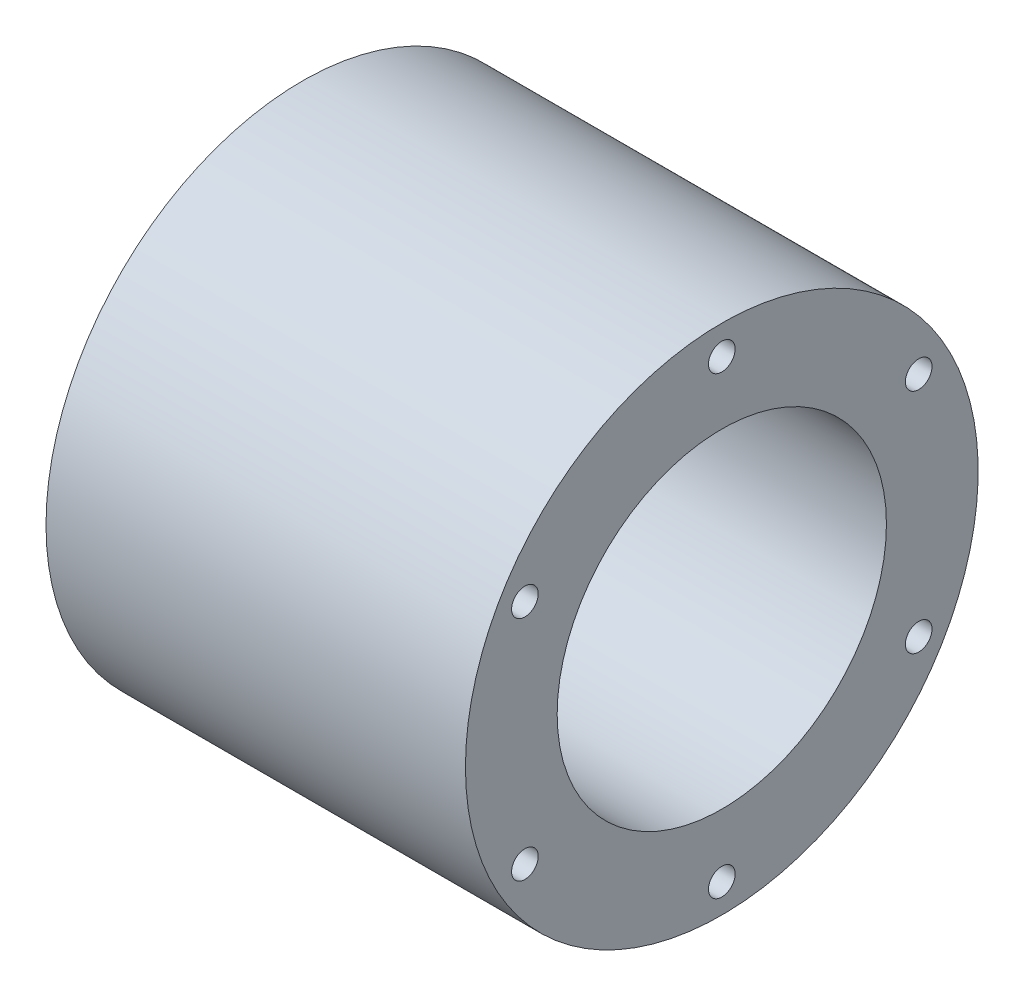
SolidWorks part; units mm, degrees
material "6063-T5"
ref_plane "Front" through (0, 0, 0) normal (0, 0, 1) x (1, 0, 0)
ref_plane "Top" through (0, 0, 0) normal (0, 1, 0) x (1, 0, 0)
ref_plane "Right" through (0, 0, 0) normal (1, 0, 0) x (0, 0, -1)
sketch "Croquis1" plane through (0, 0, 0) normal (1, 0, 0) x (0, 0, -1)
  circle A0 centre (0, 0) radius 21
  circle A1 centre (0, 0) radius 32.7
  dimension "D1" = 42
  dimension "D2" = 65.4
extrude "Saliente-Extruir1" add sketch "Croquis1" along normal mid plane 48.5
sketch "Croquis3" plane through (-24.25, 0, 0) normal (-1, 0, 0) x (0, 0, 1)
  line L6 (-18, -21) -> (18, -21)
  line L15 (-21, -18) -> (-21, 18)
  line L16 (-18, 21) -> (18, 21)
  line L17 (21, -18) -> (21, 18)
  line L18 (-21, -21) -> (21, 21) construction
  line L19 (-21, 21) -> (21, -21) construction
  circle A0 centre (0, 0) radius 32.7 construction
  circle A1 centre (0, 0) radius 32.7
  arc A2 (-18, -21) -> (-21, -18) centre (-18, -18) cw
  arc A3 (18, -21) -> (21, -18) centre (18, -18) ccw
  arc A4 (18, 21) -> (21, 18) centre (18, 18) cw
  arc A5 (-21, 18) -> (-18, 21) centre (-18, 18) cw
  dimension "D2" = 3
  dimension "D1" = 42
extrude "Saliente-Extruir3" add sketch "Croquis3" along normal blind 5
sketch "Croquis4" plane through (-24.25, 0, 0) normal (-1, 0, 0) x (0, 0, 1)
  line L1 (-15.5, -15.5) -> (15.5, -15.5) construction
  line L2 (-15.5, -15.5) -> (-15.5, 15.5) construction
  line L3 (-15.5, 15.5) -> (15.5, 15.5) construction
  line L4 (15.5, -15.5) -> (15.5, 15.5) construction
  line L5 (-15.5, -15.5) -> (15.5, 15.5) construction
  line L6 (-15.5, 15.5) -> (15.5, -15.5) construction
  circle A0 centre (15.5, 15.5) radius 3.5
  circle A1 centre (-15.5, 15.5) radius 3.5
  circle A2 centre (-15.5, -15.5) radius 3.5
  circle A3 centre (15.5, -15.5) radius 3.5
  point P0 (0, 0)
  dimension "D2" = 7
  dimension "D1" = 31
extrude "Cortar-Extruir1" cut sketch "Croquis4" against normal blind 6
hole_wizard "Taladro de margen para M31" positions "Croquis5" profile "Croquis7" hole size "M3" standard "Ansi Metric"
sketch "Croquis5" plane through (24.25, 0, 0) normal (1, 0, 0) x (0, 0, -1)
  line L0 (0, 29.425) -> (0, -29.425) construction
  line L1 (29.425, 0) -> (-29.425, 0) construction
  point P0 (0, 29)
  point P12 (25.1147, 14.5)
  point P13 (25.1147, -14.5)
  point P14 (0, -29)
  point P15 (-25.1147, -14.5)
  point P16 (-25.1147, 14.5)
  dimension "D1" = 29
  dimension "D3" = 29
  dimension "D2" = 6
sketch "Croquis7" plane through (24.25, 29, 0) normal (0, 1, 0) x (0, 0, -1)
  line L0 (0, 0) -> (0, 11.0215)
  line L1 (0, 11.0215) -> (1.7, 10)
  line L2 (1.7, 10) -> (1.7, 0)
  line L5 (1.7, 0) -> (0, 0)
  line L10 (0, 11.0215) -> (-1.7, 10) construction
  line L11 (0, -6.35) -> (0, 107.95) construction
  dimension "Diámetro de taladro" = 3.4
  dimension "Profundidad de taladro" = 10
  dimension "Ángulo de perforador" = 118
